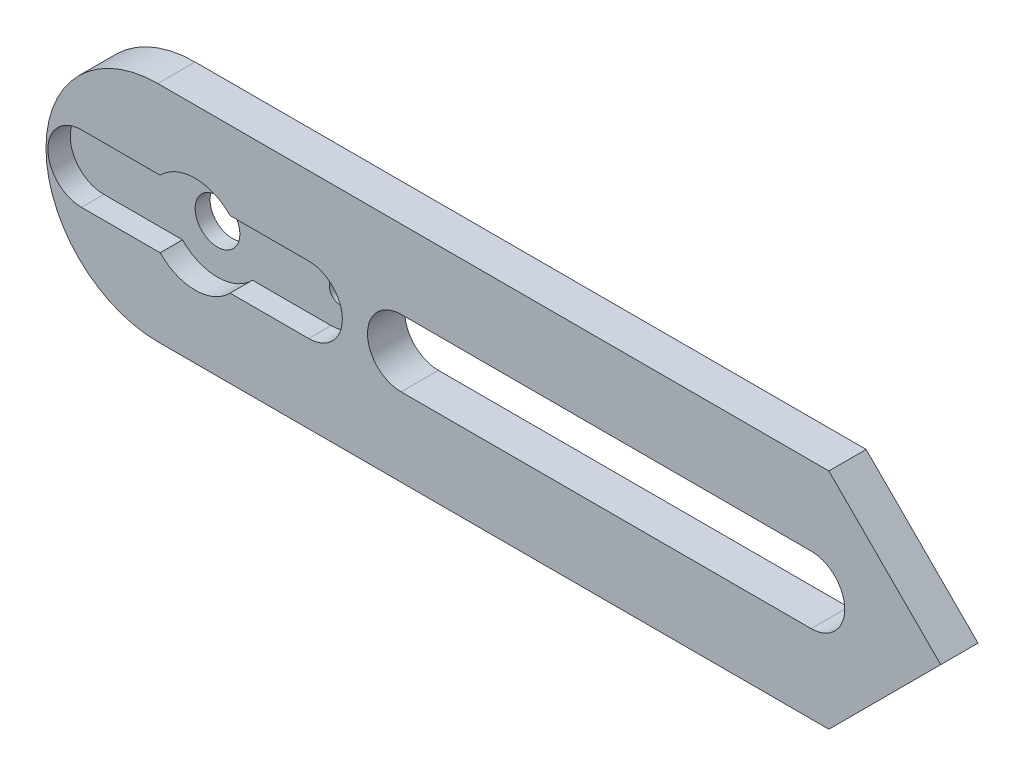
SolidWorks part; units mm, degrees
ref_plane "Front Plane" through (0, 0, 0) normal (0, 0, 1) x (1, 0, 0)
ref_plane "Top Plane" through (0, 0, 0) normal (0, 1, 0) x (1, 0, 0)
ref_plane "Right Plane" through (0, 0, 0) normal (1, 0, 0) x (0, 0, -1)
sketch "Sketch1" plane through (0, 0, 0) normal (0, 0, 1) x (1, 0, 0)
  line L3 (40, -15) -> (55, 0)
  line L4 (55, 0) -> (40, 15)
  line L5 (40, 15) -> (-50, 15)
  line L6 (40, -15) -> (-50, -15)
  arc A2 (-50, 15) -> (-50, -15) centre (-50, 0) ccw
  point P8 (40, 0)
  dimension "D1" = 90
extrude "Boss-Extrude1" add sketch "Sketch1" along normal blind 5 contours A2 L6 L3 L4 L5
sketch "Sketch2" plane through (0, 0, 5) normal (0, 0, 1) x (1, 0, 0)
  circle A0 centre (-45, 0) radius 3
  circle A1 centre (-28.5, 0) radius 1.5
  point P0 (-45, 0)
  point P1 (-50, 0)
  point P2 (-28.5, 0)
  point P8 (-38.4483, 0.0179)
extrude "Cut-Extrude1" cut sketch "Sketch2" against normal blind 5
sketch "Sketch3" plane through (0, 0, 5) normal (0, 0, 1) x (1, 0, 0)
  circle A0 centre (-45, 0) radius 6.5
extrude "Cut-Extrude2" cut sketch "Sketch3" against normal blind 3
sketch "Sketch4" plane through (0, 0, 5) normal (0, 0, 1) x (1, 0, 0)
  line L0 (-29.7555, 0) -> (-60.2445, 0) construction
  line L1 (-29.7555, -4.5) -> (-60.2445, -4.5)
  line L2 (-29.7555, 4.5) -> (-60.2445, 4.5)
  arc A0 (-29.7555, -4.5) -> (-29.7555, 4.5) centre (-29.7555, 0) ccw
  arc A1 (-60.2445, 4.5) -> (-60.2445, -4.5) centre (-60.2445, 0) ccw
  point P2 (-45, 0)
extrude "Cut-Extrude3" cut sketch "Sketch4" against normal blind 3
sketch "Sketch5" plane through (0, 0, 5) normal (0, 0, 1) x (1, 0, 0)
  point P0 (-45, 0)
  point P1 (55, 0)
sketch "Sketch6" plane through (0, 0, 5) normal (0, 0, 1) x (1, 0, 0)
  line L0 (-17.3786, 0) -> (37.6214, 0) construction
  line L1 (-17.3786, 4.5) -> (37.6214, 4.5)
  line L2 (-17.3786, -4.5) -> (37.6214, -4.5)
  arc A0 (-17.3786, 4.5) -> (-17.3786, -4.5) centre (-17.3786, 0) ccw
  arc A1 (37.6214, -4.5) -> (37.6214, 4.5) centre (37.6214, 0) ccw
  point P2 (10.1214, 0)
extrude "Cut-Extrude4" cut sketch "Sketch6" against normal blind 5
